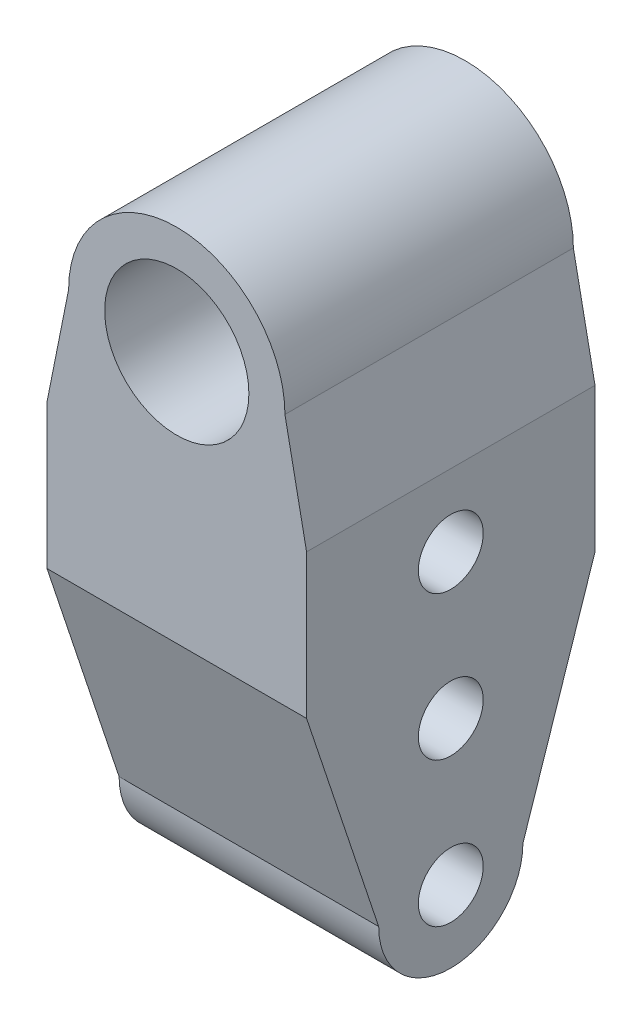
SolidWorks part; units mm, degrees
ref_plane "前视基准面" through (0, 0, 0) normal (0, 0, 1) x (1, 0, 0)
ref_plane "上视基准面" through (0, 0, 0) normal (0, 1, 0) x (1, 0, 0)
ref_plane "右视基准面" through (0, 0, 0) normal (1, 0, 0) x (0, 0, -1)
sketch "草图1" plane through (0, 0, 0) normal (0, 0, 1) x (1, 0, 0)
  line L0 (0, 15) -> (0, -75) construction
  line L1 (0, -75) -> (18, -75)
  line L2 (0, -75) -> (-18, -75)
  line L3 (-18, -75) -> (-18, -15)
  line L4 (-18, -15) -> (-15, 0)
  line L5 (18, -75) -> (18, -15)
  line L6 (18, -15) -> (15, 0)
  arc A0 (15, 0) -> (-15, 0) centre (0, 0) ccw
  circle A1 centre (0, 0) radius 10
extrude "凸台-拉伸1" add sketch "草图1" along normal mid plane 40
sketch "草图2" plane through (0, 0, 0) normal (1, 0, 0) x (0, 0, -1)
  line L0 (0, -75) -> (0, -45) construction
  line L1 (-20, -75) -> (20, -75) construction
  line L2 (0, -45) -> (0, -25) construction
  line L3 (-20, 15) -> (-20, -15) construction
  line L4 (-20, -75) -> (-20, -15) construction
  line L5 (-20, -15) -> (-20, 0) construction
  line L6 (-20, -15) -> (-20, -35) construction
  line L7 (20, -15) -> (20, -35) construction
  line L8 (0, -45) -> (0, -65) construction
  line L9 (20, -75) -> (20, -15) construction
  line L10 (-20, -35) -> (-10, -65)
  line L11 (20, -35) -> (10, -65)
  circle A0 centre (0, -45) radius 4.5
  circle A1 centre (0, -25) radius 4.5
  circle A3 centre (0, -65) radius 4.5
  arc A4 (-10, -65) -> (10, -65) centre (0, -65) ccw
extrude "切除-拉伸1" cut sketch "草图2" against normal mid plane 40 contours A1 | A0 | A3
sketch "草图7" plane through (18, 0, 0) normal (1, 0, 0) x (0, 0, -1)
  line L0 (-20, -15) -> (-20, -35) construction
  line L1 (-20, -75) -> (-20, -15) construction
  line L2 (-20, -35) -> (-10, -65)
  line L3 (20, -15) -> (20, -35) construction
  line L4 (20, -75) -> (20, -15) construction
  line L5 (20, -35) -> (10, -65)
  arc A0 (-10, -65) -> (10, -65) centre (0, -65) ccw
extrude "切除-拉伸2" cut sketch "草图7" against normal through all and the other way through all
sketch "草图8" plane through (0, 0, 0) normal (0, 0, 1) x (1, 0, 0)
  line L0 (0, 0) -> (0, -100)
